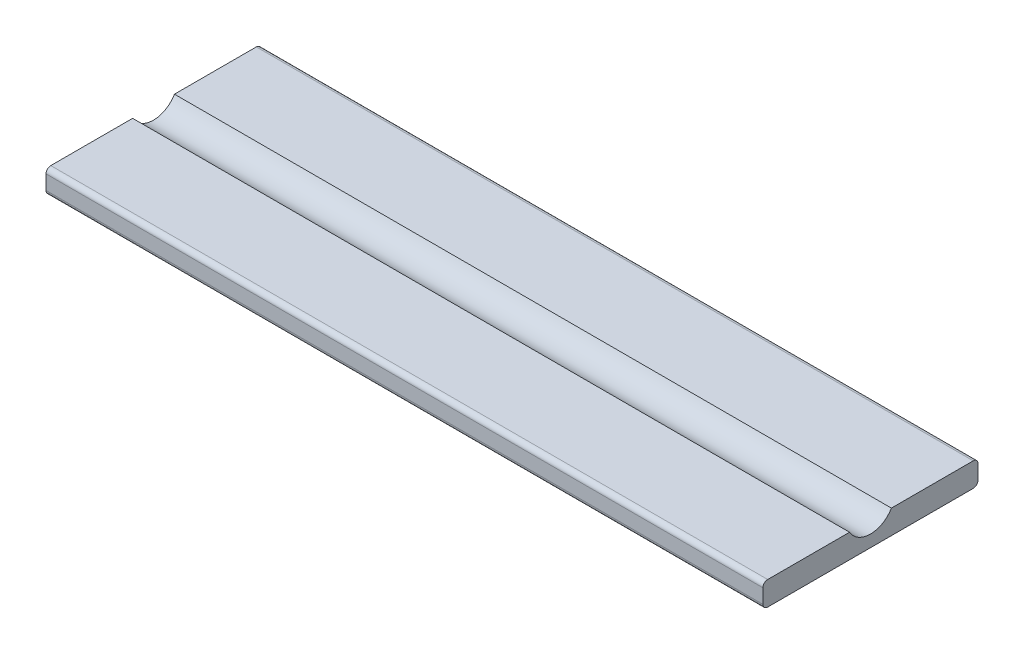
SolidWorks part; units mm, degrees
ref_plane "Front" through (0, 0, 0) normal (0, 0, 1) x (1, 0, 0)
ref_plane "Top" through (0, 0, 0) normal (0, 1, 0) x (1, 0, 0)
ref_plane "Right" through (0, 0, 0) normal (1, 0, 0) x (0, 0, -1)
sketch "Sketch2" plane through (0, 0, 0) normal (1, 0, 0) x (0, 0, -1)
  line L0 (-14.2875, 3.175) -> (-2.7781, 3.175)
  line L1 (-14.2875, 0) -> (14.2875, 0)
  line L2 (-14.2875, 0) -> (-14.2875, 3.175)
  line L4 (14.2875, 0) -> (14.2875, 3.175)
  line L8 (2.7781, 3.175) -> (14.2875, 3.175)
  arc A0 (-2.7781, 3.175) -> (2.7781, 3.175) centre (0, 4.7865) ccw
  point P5 (0, 1.5748)
  dimension "Open Width" = 28.575
  dimension "Thickness" = 3.175
  dimension "Middle Width" = 5.5562
  dimension "Middle Dp" = 1.6002
extrude "Extrude1" add sketch "Sketch2" along normal mid plane 95.25
fillet "Fillet1" radius 0.635 4 edges at (0, 0, 14.2875) (0, 3.175, 14.2875) (0, 0, -14.2875) (0, 3.175, -14.2875)
